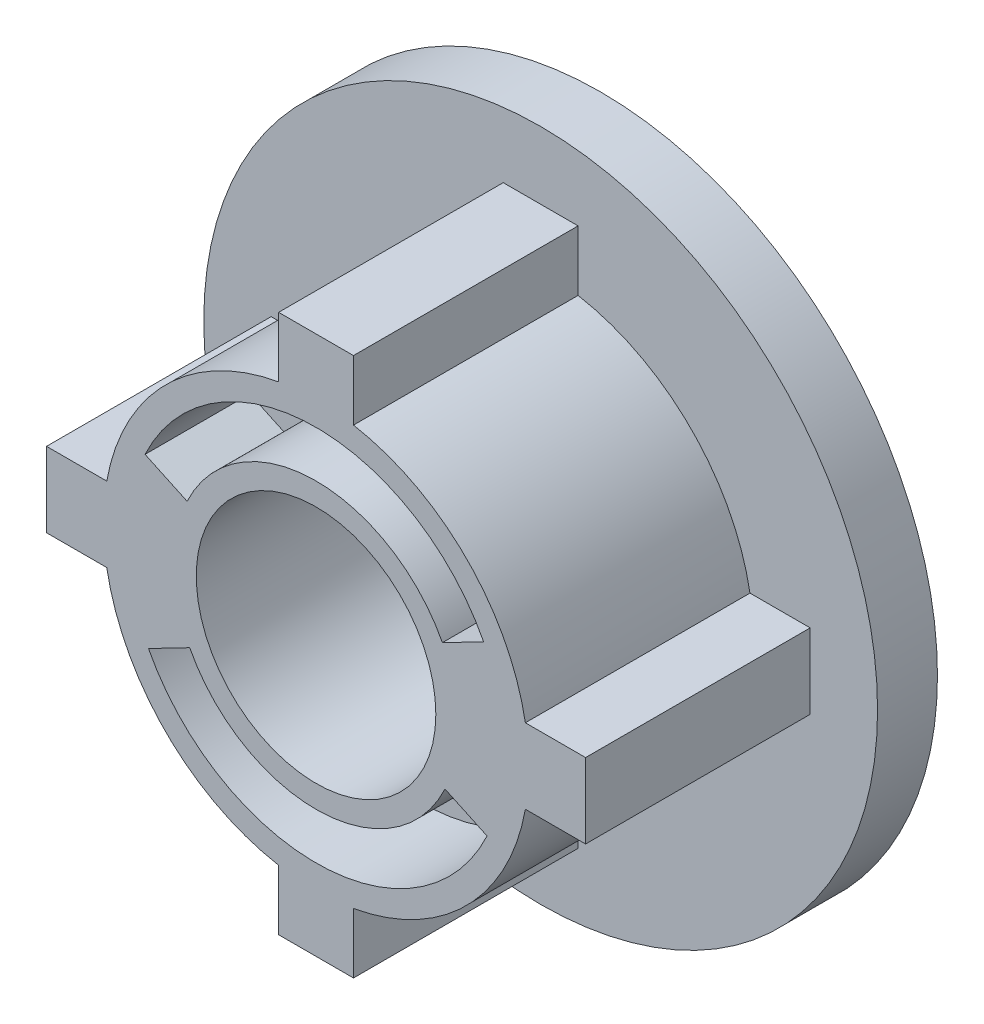
SolidWorks part; units mm, degrees
ref_plane "Plano frontal" through (0, 0, 0) normal (0, 0, 1) x (1, 0, 0)
ref_plane "Plano superior" through (0, 0, 0) normal (0, 1, 0) x (1, 0, 0)
ref_plane "Plano direito" through (0, 0, 0) normal (1, 0, 0) x (0, 0, -1)
sketch "Esboço1" plane through (0, 0, 0) normal (0, 0, 1) x (1, 0, 0)
  line L0 (18, 2.5) -> (13.9782, 2.5)
  line L1 (18, -2.5) -> (18, 2.5)
  line L2 (13.9782, -2.5) -> (18, -2.5)
  line L3 (2.5, -18) -> (2.5, -13.9782)
  line L4 (-2.5, -18) -> (2.5, -18)
  line L5 (-2.5, -13.9782) -> (-2.5, -18)
  line L6 (-18, -2.5) -> (-13.9782, -2.5)
  line L7 (-18, 2.5) -> (-18, -2.5)
  line L8 (-13.9782, 2.5) -> (-18, 2.5)
  line L9 (-2.5, 18) -> (-2.5, 13.9782)
  line L10 (2.5, 18) -> (-2.5, 18)
  line L11 (2.5, 13.9782) -> (2.5, 18)
  circle A0 centre (0, 0) radius 11.15
  circle A1 centre (0, 0) radius 6.1
  circle A3 centre (0, 0) radius 4.3
  arc A4 (-13.9782, -2.5) -> (-2.5, -13.9782) centre (0, 0) ccw
  arc A5 (13.9782, 2.5) -> (2.5, 13.9782) centre (0, 0) ccw
  arc A6 (2.5, -13.9782) -> (13.9782, -2.5) centre (0, 0) ccw
  arc A7 (-13.9782, -2.5) -> (-2.5, -13.9782) centre (0, 0) ccw
  arc A8 (-2.5, 13.9782) -> (-13.9782, 2.5) centre (0, 0) ccw
  arc A9 (-2.5, 13.9782) -> (-13.9782, 2.5) centre (0, 0) ccw
  arc A10 (13.9782, 2.5) -> (2.5, 13.9782) centre (0, 0) ccw
  arc A11 (2.5, -13.9782) -> (13.9782, -2.5) centre (0, 0) ccw
  dimension "D1" = 28.4
  dimension "D2" = 8.6
  dimension "D3" = 12.2
  dimension "D5" = 22.3
  dimension "D6" = 14.2
  dimension "D7" = 14.2
  dimension "D8" = 14.2
  dimension "D9" = 14.2
  dimension "D10" = 2.5
  dimension "D11" = 2.5
  dimension "D12" = 13.9782
  dimension "D13" = 13.9782
  dimension "D14" = 18
  dimension "D15" = 18
  dimension "D16" = 2.5
  dimension "D17" = 2.5
  dimension "D18" = 13.9782
  dimension "D19" = 13.9782
  dimension "D20" = 18
  dimension "D21" = 18
  dimension "D22" = 2.5
  dimension "D23" = 2.5
  dimension "D24" = 13.9782
  dimension "D25" = 13.9782
  dimension "D26" = 18
  dimension "D27" = 18
  dimension "D28" = 2.5
  dimension "D29" = 2.5
  dimension "D30" = 13.9782
  dimension "D31" = 13.9782
  dimension "D32" = 18
  dimension "D33" = 18
extrude "Ressalto-extrusão1" add sketch "Esboço1" along normal blind 15 contours L9 A8 L8 L7 L6 A4 L5 L4 L3 A6 L2 L1 L0 A5 L11 L10 A0
sketch "Esboço2" plane through (0, 0, 0) normal (0, 0, -1) x (-1, 0, 0)
  line L4 (2.5, 18) -> (2.5, 13.9782) construction
  line L5 (-2.5, 18) -> (2.5, 18) construction
  circle A0 centre (0, 0) radius 22.5
  arc A9 (2.5, 13.9782) -> (-13.9782, -2.5) centre (0, 0) ccw
  arc A10 (-13.9782, -2.5) -> (2.5, -13.9782) centre (0, 0) ccw
  arc A11 (-2.5, -13.9782) -> (13.9782, -2.5) centre (0, 0) ccw
  arc A12 (13.9782, -2.5) -> (2.5, 13.9782) centre (0, 0) ccw
  line M18 (2.5, 13.9782) -> (2.5, 18)
  line M19 (2.5, 18) -> (-2.5, 18)
  line M20 (-2.5, 18) -> (-2.5, 13.9782)
  arc M21 (-2.5, 13.9782) -> (-13.9782, 2.5) centre (0, 0) ccw
  line M22 (-13.9782, 2.5) -> (-18, 2.5)
  line M23 (-18, 2.5) -> (-18, -2.5)
  line M24 (-18, -2.5) -> (-13.9782, -2.5)
  arc M25 (-13.9782, -2.5) -> (-2.5, -13.9782) centre (0, 0) ccw
  line M26 (-2.5, -13.9782) -> (-2.5, -18)
  line M27 (-2.5, -18) -> (2.5, -18)
  line M28 (2.5, -18) -> (2.5, -13.9782)
  arc M29 (2.5, -13.9782) -> (13.9782, -2.5) centre (0, 0) ccw
  line M30 (13.9782, -2.5) -> (18, -2.5)
  line M31 (18, -2.5) -> (18, 2.5)
  line M32 (18, 2.5) -> (13.9782, 2.5)
  arc M33 (13.9782, 2.5) -> (2.5, 13.9782) centre (0, 0) ccw
  dimension "D1" = 45
  dimension "D2" = 14.2
  dimension "D3" = 14.2
  dimension "D4" = 14.2
  dimension "D5" = 14.2
  dimension "D6" = 11.4782
  dimension "D7" = 2.5
  dimension "D8" = 5
  dimension "D9" = 16.4782
  dimension "D10" = 4.0218
  dimension "D11" = 18
  dimension "D12" = 31.9782
  dimension "D14" = 20.5
  dimension "D15" = 20.5
  dimension "D16" = 31.9782
extrude "Ressalto-extrusão2" add sketch "Esboço2" along normal blind 4 separate body contours A0 M18 M33 M32 M31 M30 M29 M28 M27 M26 M25 M24 M23 M22 M21 M20 M19 | A10 M26 M27 M28 | A9 M22 M23 M24 | A9 M18 M19 M20 | A12 M30 M31 M32
sketch "Esboço5" plane through (0, 0, 15) normal (0, 0, 1) x (1, 0, 0)
  circle A0 centre (0, 0) radius 11.15 construction
  circle A1 centre (0, 0) radius 11.15
  circle A2 centre (0, 0) radius 8
  dimension "D1" = 16
extrude "Ressalto-extrusão6" add sketch "Esboço5" against normal blind 8
sketch "Esboço7" plane through (0, 0, 0) normal (0, 0, -1) x (-1, 0, 0)
  circle A0 centre (0, 0) radius 11.15 construction
  circle A1 centre (0, 0) radius 14.2 construction
  circle A2 centre (0, 0) radius 11.15
  circle A3 centre (0, 0) radius 14.2
extrude "Ressalto-extrusão7" add sketch "Esboço7" along normal up to surface (4 mm away) up to face at (-14.2, 0, -4)
sketch "Esboço8" plane through (0, 0, 7) normal (0, 0, -1) x (-1, 0, 0)
  circle A0 centre (0, 0) radius 8 construction
  circle A1 centre (0, 0) radius 11.15 construction
  circle A2 centre (0, 0) radius 8
  circle A3 centre (0, 0) radius 11.15
extrude "Ressalto-extrusão8" add sketch "Esboço8" along normal blind 4
sketch "Esboço11" plane through (0, 0, 15) normal (0, 0, 1) x (1, 0, 0)
  line L0 (-11.1912, -5.7895) -> (-8.4378, -4.3651)
  line L1 (-11.4195, 5.325) -> (-8.6099, 4.0149)
  line L2 (8.6099, -4.0149) -> (11.4195, -5.325)
  line L3 (8.4378, 4.3651) -> (11.1912, 5.7895)
  arc A2 (-8.4378, -4.3651) -> (8.6099, -4.0149) centre (0, 0) ccw
  arc A3 (-11.1912, -5.7895) -> (11.4195, -5.325) centre (0, 0) ccw
  arc A4 (8.4378, 4.3651) -> (-8.6099, 4.0149) centre (0, 0) ccw
  arc A5 (11.1912, 5.7895) -> (-11.4195, 5.325) centre (0, 0) ccw
  dimension "D1" = 19
  dimension "D2" = 25.2
extrude "Corte-extrusão1" cut sketch "Esboço11" against normal blind 7
